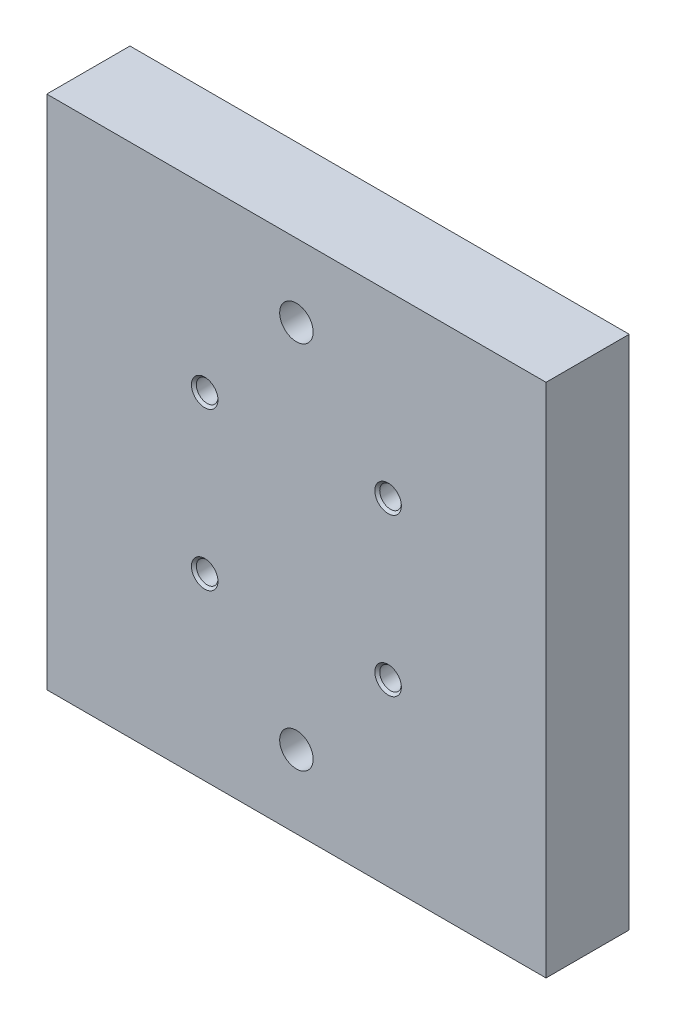
SolidWorks part; units mm, degrees
ref_plane "Front Plane" through (0, 0, 0) normal (0, 0, 1) x (1, 0, 0)
ref_plane "Top Plane" through (0, 0, 0) normal (0, 1, 0) x (1, 0, 0)
ref_plane "Right Plane" through (0, 0, 0) normal (1, 0, 0) x (0, 0, -1)
sketch "Sketch1" plane through (0, 0, 0) normal (0, 0, 1) x (1, 0, 0)
  line L0 (0, 39.37) -> (0, -39.37) construction
  line L1 (-38.1, -39.37) -> (38.1, -39.37)
  line L2 (-38.1, -39.37) -> (-38.1, 39.37)
  line L3 (-38.1, 39.37) -> (38.1, 39.37)
  line L4 (38.1, -39.37) -> (38.1, 39.37)
  line L5 (-38.1, 0) -> (38.1, 0) construction
  point P8 (0, 0)
  dimension "D1" = 78.74
  dimension "D2" = 76.2
extrude "Boss-Extrude1" add sketch "Sketch1" along normal blind 12.7
hole_wizard "Tap Drill for 1/4-20 Tap1" positions "Sketch2" profile "Sketch3" hole size "1/4-20" standard "ANSI Inch"
sketch "Sketch2" plane through (0, 0, 0) normal (0, 0, 1) x (1, 0, 0)
  line L0 (0, 38.1) -> (0, -38.1) construction
  line L2 (38.1, 0) -> (-38.1, 0) construction
  point P0 (-28.575, 28.575)
  point P13 (28.575, 28.575)
  point P14 (-28.575, -28.575)
  point P15 (28.575, -28.575)
  dimension "D1" = 28.575
  dimension "D2" = 28.575
sketch "Sketch3" plane through (-28.575, 28.575, 0) normal (1, 0, 0) x (0, 1, 0)
  line L0 (0, 0) -> (0, 12.7)
  line L1 (0, 12.7) -> (2.5527, 12.7)
  line L2 (2.5527, 12.7) -> (2.5527, 0)
  line L5 (2.5527, 0) -> (0, 0)
  line L11 (0, -6.35) -> (0, 107.95) construction
  dimension "Thru Hole Dia." = 5.1054
  dimension "Thru Hole Depth" = 12.7
hole_wizard "1/4-20 Tapped Hole1" positions "Sketch6" profile "Sketch7" tap size "1/4-20" standard "ANSI Inch" end condition through all
sketch "Sketch6" plane through (0, 0, 0) normal (0, 0, -1) x (-1, 0, 0)
  line L0 (0, 39.37) -> (0, -39.37) construction
  line L1 (-38.1, 0) -> (38.1, 0) construction
  point P0 (0, 28.2321)
  point P10 (0, -28.2321)
  dimension "D1" = 56.4642
sketch "Sketch7" plane through (0, 28.2321, 0) normal (1, 0, 0) x (0, 1, 0)
  line L0 (0, 0) -> (0, 12.7)
  line L1 (0, 12.7) -> (2.5527, 12.7)
  line L2 (2.5527, 12.7) -> (2.5527, 1.2573)
  line L3 (2.5527, 1.2573) -> (3.81, 0)
  line L5 (3.81, 0) -> (0, 0)
  line L6 (-2.5527, 1.2573) -> (-3.81, 0) construction
  line L11 (0, -6.35) -> (0, 107.95) construction
  dimension "Thru Tap Drill Dia." = 5.1054
  dimension "Thru Tap Drill Depth" = 12.7
  dimension "Near C'Sink Dia." = 7.62
  dimension "Near C'Sink Angle" = 90
hole_wizard "M4 Tapped Hole1" positions "Sketch4" profile "Sketch5" tap size "M4" standard "ISO" end condition through all
sketch "Sketch4" plane through (0, 0, 0) normal (0, 0, -1) x (-1, 0, 0)
  line L0 (-38.1, 0) -> (38.1, 0) construction
  line L2 (0, 39.37) -> (0, -39.37) construction
  point P0 (-13.9954, 11.9888)
  point P13 (13.9954, 11.9888)
  point P14 (13.9954, -11.9888)
  point P15 (-13.9954, -11.9888)
  dimension "D1" = 13.9954
  dimension "D2" = 11.9888
sketch "Sketch5" plane through (13.9954, 11.9888, 0) normal (1, 0, 0) x (0, 1, 0)
  line L0 (0, 0) -> (0, 12.7)
  line L1 (0, 12.7) -> (2.025, 12.7)
  line L2 (1.65, 12.325) -> (1.65, 0.375)
  line L3 (1.65, 0.375) -> (2.025, 0)
  line L5 (2.025, 0) -> (0, 0)
  line L6 (-1.65, 0.375) -> (-2.025, 0) construction
  line L7 (2.025, 12.7) -> (1.65, 12.325)
  line L8 (-2.025, 12.7) -> (-1.65, 12.325) construction
  line L11 (0, -6.35) -> (0, 107.95) construction
  dimension "Thru Tap Drill Dia." = 3.3
  dimension "Thru Tap Drill Depth" = 12.7
  dimension "Near C'Sink Dia." = 4.05
  dimension "Near C'Sink Angle" = 90
  dimension "Far C'Sink Dia." = 4.05
  dimension "Far C'Sink Angle" = 90
